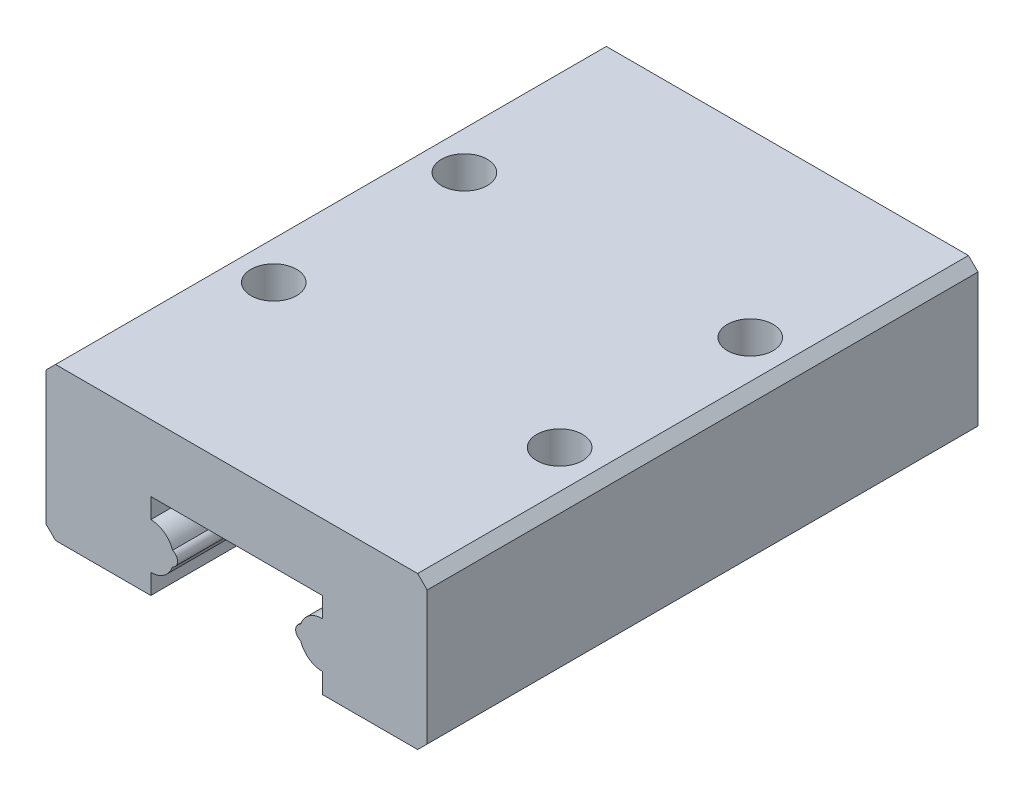
SolidWorks part; units mm, degrees
ref_plane "前视基准面" through (0, 0, 0) normal (0, 0, 1) x (1, 0, 0)
ref_plane "上视基准面" through (0, 0, 0) normal (0, 1, 0) x (1, 0, 0)
ref_plane "右视基准面" through (0, 0, 0) normal (1, 0, 0) x (0, 0, -1)
other "Configuration Table"
sketch "草图1" plane through (0, 0, 0) normal (0, 0, 1) x (1, 0, 0)
  line L0 (-19.5, 8) -> (-20, 7.5)
  line L1 (-0.5, 0) -> (-5.5, 0)
  line L2 (0, 0.5) -> (0, 7.5)
  line L3 (-0.5, 8) -> (-19.5, 8)
  line L4 (-20, 0.5) -> (-20, 7.5)
  line L5 (-19.5, 0) -> (-20, 0.5)
  line L6 (0, 0.5) -> (-0.5, 0)
  line L7 (0, 7.5) -> (-0.5, 8)
  line L8 (-14.5, 0) -> (-19.5, 0)
  line L10 (-14.5, 0) -> (-14.5, 1.05)
  line L11 (-14.5, 4.5) -> (-5.5, 4.5)
  line L12 (-5.5, 0) -> (-5.5, 1.05)
  line L13 (-14.5, 3.45) -> (-14.5, 4.5)
  line L15 (-5.5, 3.45) -> (-5.5, 4.5)
  arc A0 (-14.5, 1.05) -> (-13.36, 1.8753) centre (-14.5, 2.25) ccw
  arc A1 (-13.36, 1.8753) -> (-13.36, 2.6247) centre (-13.5, 2.25) ccw
  arc A2 (-13.36, 2.6247) -> (-14.5, 3.45) centre (-14.5, 2.25) ccw
  arc A3 (-5.5, 1.05) -> (-6.64, 1.8753) centre (-5.5, 2.25) cw
  arc A4 (-6.64, 1.8753) -> (-6.64, 2.6247) centre (-6.5, 2.25) cw
  arc A5 (-6.64, 2.6247) -> (-5.5, 3.45) centre (-5.5, 2.25) cw
  point P0 (0, 0)
  point P1 (-20, 8)
  point P2 (0, 8)
  point P3 (-20, 0)
  point P17 (-10, 4.5)
  point P18 (-10, 8)
  dimension "D10" = 2.4
  dimension "D11" = 0.8
  dimension "D1" = 20
  dimension "D2" = 8
  dimension "D3" = 9
  dimension "D4" = 2.25
  dimension "D9" = 1
  dimension "D12" = 2.25
extrude "凸台-拉伸1" add sketch "草图1" against normal blind 28.9 contours L4 L0 L3 L7 L2 L6 L1 L12 A3 A4 A5 L15 L11 L13 A2 A1 A0 L10 L8 L5
sketch "草图2" plane through (0, 8, 0) normal (0, 1, 0) x (1, 0, 0)
  circle A0 centre (-17.5, 19.45) radius 1.2
  circle A1 centre (-2.5, 19.45) radius 1.2
  circle A2 centre (-2.5, 9.45) radius 1.2
  circle A3 centre (-17.5, 9.45) radius 1.2
  dimension "D1" = 2.4
  dimension "D4" = 10
  dimension "D5" = 15
  dimension "D2" = 2
  dimension "D3" = 2
extrude "切除-拉伸1" cut sketch "草图2" against normal blind 5
